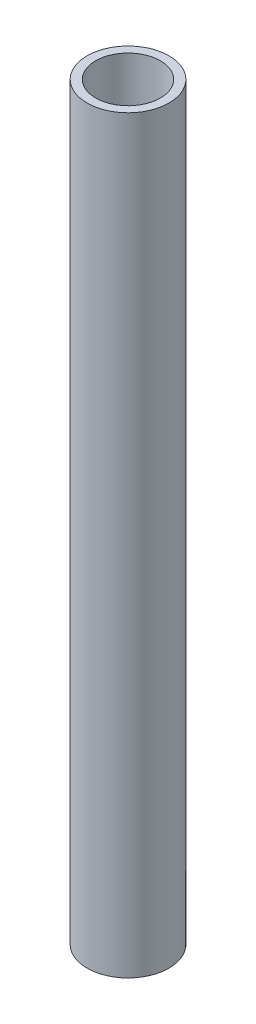
SolidWorks part; units mm, degrees
ref_plane "Front Plane" through (0, 0, 0) normal (0, 0, 1) x (1, 0, 0)
ref_plane "Top Plane" through (0, 0, 0) normal (0, 1, 0) x (1, 0, 0)
ref_plane "Right Plane" through (0, 0, 0) normal (1, 0, 0) x (0, 0, -1)
sketch "Sketch1" plane through (0, 0, 0) normal (0, 1, 0) x (1, 0, 0)
  circle A0 centre (0, 0) radius 16.65
  circle A1 centre (0, 0) radius 13.15
  dimension "D1" = 26.3
  dimension "D2" = 33.3
extrude "Boss-Extrude1" add sketch "Sketch1" along normal blind 304.8
